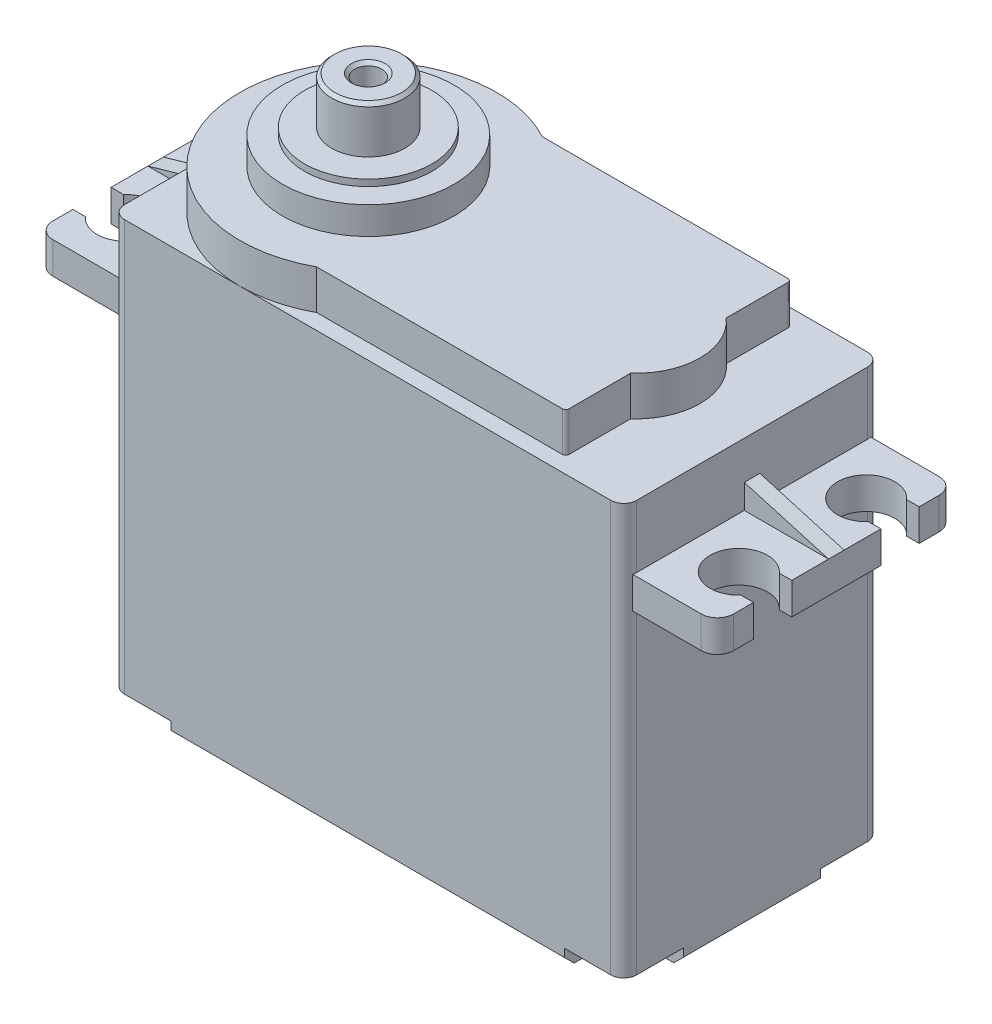
SolidWorks part; units mm, degrees
ref_plane "Front Plane" through (0, 0, 0) normal (0, 0, 1) x (1, 0, 0)
ref_plane "Top Plane" through (0, 0, 0) normal (0, 1, 0) x (1, 0, 0)
ref_plane "Right Plane" through (0, 0, 0) normal (1, 0, 0) x (0, 0, -1)
sketch "Sketch1" plane through (0, 0, 0) normal (0, 1, 0) x (1, 0, 0)
  line L0 (0, 9.0424) -> (0, -9.0424)
  line L1 (1.016, -10.0584) -> (39.116, -10.0584)
  line L2 (40.132, -9.0424) -> (40.132, 9.0424)
  line L3 (39.116, 10.0584) -> (1.016, 10.0584)
  arc A0 (39.116, 10.0584) -> (40.132, 9.0424) centre (39.116, 9.0424) cw
  arc A1 (40.132, -9.0424) -> (39.116, -10.0584) centre (39.116, -9.0424) cw
  arc A2 (1.016, -10.0584) -> (0, -9.0424) centre (1.016, -9.0424) cw
  arc A3 (0, 9.0424) -> (1.016, 10.0584) centre (1.016, 9.0424) cw
  point P7 (40.132, 10.0584)
  point P12 (0, -10.0584)
  point P15 (0, 10.0584)
  dimension "D4" = 1.016
  dimension "D1" = 20.1168
  dimension "D2" = 10.0584
  dimension "D3" = 40.132
extrude "Boss-Extrude1" add sketch "Sketch1" along normal blind 33.6042
sketch "Sketch2" plane through (0, 0, 0) normal (0, -1, 0) x (1, 0, 0)
  line L0 (20.066, 10.0584) -> (20.066, -10.0584) construction
  line L1 (1.016, 10.0584) -> (39.116, 10.0584) construction
  line L2 (39.116, -10.0584) -> (1.016, -10.0584) construction
  line L3 (0, 0) -> (40.132, 0) construction
  line L4 (40.132, 9.0424) -> (40.132, -9.0424) construction
  line L5 (4.6482, 10.0584) -> (4.6482, 7.3533)
  line L6 (35.4838, 10.0584) -> (35.4838, 7.3533)
  line L7 (0, -5.3721) -> (2.667, -5.3721)
  line L8 (0, 5.3721) -> (2.667, 5.3721)
  line L9 (37.465, 5.3721) -> (40.132, 5.3721)
  line L10 (4.6482, -7.3533) -> (4.6482, -10.0584)
  line L11 (0, 5.3721) -> (40.132, 5.3721) construction
  line L12 (37.465, -5.3721) -> (40.132, -5.3721)
  line L13 (4.6482, 10.0584) -> (4.6482, -10.0584) construction
  line L14 (35.4838, -7.3533) -> (35.4838, -10.0584)
  line L15 (0, -5.3721) -> (40.132, -5.3721) construction
  line L16 (0, -5.3721) -> (0, -9.0424)
  line L17 (35.4838, 10.0584) -> (35.4838, -10.0584) construction
  line L18 (35.4838, -10.0584) -> (39.116, -10.0584)
  line L19 (40.132, 5.3721) -> (40.132, 9.0424)
  line L20 (4.6482, 10.0584) -> (1.016, 10.0584)
  line L21 (40.132, -9.0424) -> (40.132, 9.0424)
  line L22 (39.116, 10.0584) -> (1.016, 10.0584)
  line L23 (0, 9.0424) -> (0, -9.0424)
  line L24 (1.016, -10.0584) -> (39.116, -10.0584)
  line L25 (40.132, -9.0424) -> (40.132, -5.3721)
  line L26 (39.116, 10.0584) -> (35.4838, 10.0584)
  line L27 (0, 9.0424) -> (0, 5.3721)
  line L28 (1.016, -10.0584) -> (4.6482, -10.0584)
  arc A0 (2.667, -5.3721) -> (4.6482, -7.3533) centre (2.667, -7.3533) cw
  arc A1 (35.4838, -7.3533) -> (37.465, -5.3721) centre (37.465, -7.3533) cw
  arc A2 (37.465, 5.3721) -> (35.4838, 7.3533) centre (37.465, 7.3533) cw
  arc A3 (4.6482, 7.3533) -> (2.667, 5.3721) centre (2.667, 7.3533) cw
  arc A8 (39.116, -10.0584) -> (40.132, -9.0424) centre (39.116, -9.0424) ccw
  arc A9 (40.132, 9.0424) -> (39.116, 10.0584) centre (39.116, 9.0424) ccw
  arc A10 (1.016, 10.0584) -> (0, 9.0424) centre (1.016, 9.0424) ccw
  arc A11 (0, -9.0424) -> (1.016, -10.0584) centre (1.016, -9.0424) ccw
  arc A12 (39.116, -10.0584) -> (40.132, -9.0424) centre (39.116, -9.0424) ccw
  arc A13 (40.132, 9.0424) -> (39.116, 10.0584) centre (39.116, 9.0424) ccw
  arc A14 (1.016, 10.0584) -> (0, 9.0424) centre (1.016, 9.0424) ccw
  arc A15 (0, -9.0424) -> (1.016, -10.0584) centre (1.016, -9.0424) ccw
  point P27 (35.4838, -5.3721)
  dimension "D5" = 1.9812
  dimension "D1" = 15.4178
  dimension "D2" = 15.4178
  dimension "D3" = 5.3721
  dimension "D4" = 5.3721
  dimension "D6" = 0
extrude "Cut-Extrude1" cut sketch "Sketch2" against normal blind 1.397
chamfer "Chamfer1" distance 0.762 angle 45 4 edges at (0, 0, 0) (20.066, 0, -10.0584) (40.132, 0, 0) (20.066, 0, 10.0584)
sketch "Sketch3" plane through (40.132, 0, 0) normal (1, 0, 0) x (0, 0, -1)
  line L1 (-9.3218, 28.702) -> (9.3218, 28.702)
  line L2 (-9.0424, 26.2128) -> (9.0424, 26.2128)
  line L3 (-9.3218, 26.2128) -> (9.3218, 26.2128)
  line L4 (0, 39.7789) -> (0, -7.6498) construction
  line L5 (-9.3218, 28.702) -> (-9.3218, 26.2128)
  line L6 (9.3218, 28.702) -> (9.3218, 26.2128)
  line L7 (-9.0424, 28.702) -> (9.0424, 28.702) construction
  line L8 (-9.3218, 39.7789) -> (-9.3218, -7.6498) construction
  line L9 (-9.0424, 26.2128) -> (9.0424, 26.2128) construction
  line L10 (9.3218, 39.7789) -> (9.3218, -7.6498) construction
  dimension "D1" = 7.3914
  dimension "D2" = 9.3218
  dimension "D3" = 2.4892
  dimension "D4" = 9.3218
extrude "Boss-Extrude2" add sketch "Sketch3" along normal mid plane 13.208
sketch "Sketch4" plane through (0, 0, 0) normal (-1, 0, 0) x (0, 0, 1)
  line L0 (9.0424, 26.2128) -> (-9.0424, 26.2128) construction
  line L1 (-9.3218, 26.2128) -> (-9.3218, 28.702) construction
  line L2 (-9.0424, 28.702) -> (9.0424, 28.702) construction
  line L3 (9.3218, 28.702) -> (9.3218, 26.2128) construction
  line L4 (9.3218, 26.2128) -> (-9.3218, 26.2128)
  line L5 (-9.3218, 26.2128) -> (-9.3218, 28.702)
  line L6 (-9.3218, 28.702) -> (9.3218, 28.702)
  line L7 (9.3218, 28.702) -> (9.3218, 26.2128)
extrude "Boss-Extrude3" add sketch "Sketch4" along normal mid plane 13.208
fillet "Fillet1" radius 1.27 4 edges at (-6.604, 27.4574, 9.3218) (-6.604, 27.4574, -9.3218) (46.736, 27.4574, -9.3218) (46.736, 27.4574, 9.3218)
sketch "Sketch5" plane through (0, 28.702, 0) normal (0, 1, 0) x (1, 0, 0)
  line L0 (-9.1456, 0) -> (53.3851, 0) construction
  line L1 (20.066, 10.0584) -> (20.066, -10.0584) construction
  line L2 (39.116, 10.0584) -> (1.016, 10.0584) construction
  line L3 (1.016, -10.0584) -> (39.116, -10.0584) construction
  line L4 (-9.1456, -4.9911) -> (-3.9497, -4.9911) construction
  line L5 (-9.1456, 4.9911) -> (-3.9497, 4.9911) construction
  line L6 (-3.9497, 10.0584) -> (-3.9497, 4.9911) construction
  line L7 (44.0817, 10.0584) -> (44.0817, 4.9911) construction
  line L8 (-3.9497, -4.9911) -> (-3.9497, -10.0584) construction
  line L9 (44.0817, -4.9911) -> (44.0817, -10.0584) construction
  line L10 (-3.9497, 10.0584) -> (-3.9497, -10.0584) construction
  line L11 (44.0817, -4.9911) -> (53.3851, -4.9911) construction
  line L12 (44.0817, 10.0584) -> (44.0817, -10.0584) construction
  line L13 (44.0817, 4.9911) -> (53.3851, 4.9911) construction
  line L14 (-9.1456, -4.9911) -> (53.3851, -4.9911) construction
  line L15 (-6.604, 3.4925) -> (-5.6252, 3.4925)
  line L16 (-9.1456, 4.9911) -> (53.3851, 4.9911) construction
  line L17 (-6.604, -6.4897) -> (-5.6252, -6.4897)
  line L18 (45.7572, -6.4897) -> (46.736, -6.4897)
  line L19 (45.7572, 3.4925) -> (46.736, 3.4925)
  line L20 (-6.604, 6.4897) -> (-5.6252, 6.4897)
  line L21 (-6.604, -3.4925) -> (-5.6252, -3.4925)
  line L22 (45.7572, -3.4925) -> (46.736, -3.4925)
  line L23 (45.7572, 6.4897) -> (46.736, 6.4897)
  line L24 (-6.604, -8.0518) -> (-6.604, 8.0518) construction
  line L25 (46.736, 8.0518) -> (46.736, -8.0518) construction
  line L26 (-6.604, -6.4897) -> (-6.604, -3.4925)
  line L27 (46.736, 6.4897) -> (46.736, 3.4925)
  line L28 (-9.1456, 6.4897) -> (-3.9497, 6.4897) construction
  line L29 (-9.1456, -6.4897) -> (-3.9497, -6.4897) construction
  line L30 (44.0817, -6.4897) -> (53.3851, -6.4897) construction
  line L31 (44.0817, 6.4897) -> (53.3851, 6.4897) construction
  line L32 (46.736, -3.4925) -> (46.736, -6.4897)
  line L33 (44.0817, 3.4925) -> (53.3851, 3.4925) construction
  line L34 (44.0817, -3.4925) -> (53.3851, -3.4925) construction
  line L35 (-9.1456, -3.4925) -> (-3.9497, -3.4925) construction
  line L36 (-9.1456, 3.4925) -> (-3.9497, 3.4925) construction
  line L37 (-6.604, 3.4925) -> (-6.604, 6.4897)
  arc A0 (-5.6252, 3.4925) -> (-5.6252, 6.4897) centre (-3.9497, 4.9911) ccw
  arc A1 (-5.6252, -6.4897) -> (-5.6252, -3.4925) centre (-3.9497, -4.9911) ccw
  arc A2 (45.7572, -3.4925) -> (45.7572, -6.4897) centre (44.0817, -4.9911) ccw
  arc A3 (45.7572, 6.4897) -> (45.7572, 3.4925) centre (44.0817, 4.9911) ccw
  dimension "D5" = 4.4958
  dimension "D1" = 4.9911
  dimension "D2" = 4.9911
  dimension "D3" = 24.0157
  dimension "D4" = 24.0157
  dimension "D6" = 1.4986
  dimension "D7" = 1.4986
extrude "Cut-Extrude2" cut sketch "Sketch5" against normal blind 3.048
sketch "Sketch6" plane through (0, 28.702, 0) normal (0, 1, 0) x (1, 0, 0)
  line L0 (-7.6959, 0) -> (49.9058, 0) construction
  line L1 (-6.604, -0.6096) -> (0, -0.6096)
  line L2 (-6.604, 0.6096) -> (0, 0.6096)
  line L3 (-6.604, -3.4925) -> (-6.604, 3.4925) construction
  line L4 (0, 9.0424) -> (0, -9.0424) construction
  line L5 (40.132, -9.0424) -> (40.132, 9.0424) construction
  line L6 (46.736, 3.4925) -> (46.736, -3.4925) construction
  line L7 (-6.604, -0.6096) -> (-6.604, 0.6096)
  line L8 (0, 0.6096) -> (0, -0.6096)
  line L9 (40.132, -0.6096) -> (40.132, 0.6096)
  line L10 (46.736, 0.6096) -> (46.736, -0.6096)
  line L11 (-7.6959, 0.6096) -> (49.9058, 0.6096) construction
  line L12 (-7.6959, -0.6096) -> (49.9058, -0.6096) construction
  line L13 (40.132, 0.6096) -> (46.736, 0.6096)
  line L14 (40.132, -0.6096) -> (46.736, -0.6096)
  dimension "D1" = 0.6096
  dimension "D2" = 0.6096
extrude "Boss-Extrude4" add sketch "Sketch6" along normal blind 1.905
sketch "Sketch7" plane through (0, 0, 0.6096) normal (0, 0, 1) x (1, 0, 0)
  line L0 (40.132, 30.607) -> (46.736, 28.702)
  line L1 (0, 30.607) -> (-6.604, 28.702)
  line L4 (-6.604, 28.702) -> (0, 28.702)
  line L5 (0, 28.702) -> (0, 30.607)
  line L6 (0, 30.607) -> (-6.604, 30.607)
  line L7 (-6.604, 30.607) -> (-6.604, 28.702)
  line L10 (0, 30.607) -> (-6.604, 30.607)
  line L11 (-6.604, 30.607) -> (-6.604, 28.702)
  line L12 (40.132, 28.702) -> (46.736, 28.702)
  line L13 (46.736, 28.702) -> (46.736, 30.607)
  line L14 (46.736, 30.607) -> (40.132, 30.607)
  line L15 (40.132, 30.607) -> (40.132, 28.702)
  line L17 (46.736, 28.702) -> (46.736, 30.607)
  line L18 (46.736, 30.607) -> (40.132, 30.607)
  dimension "D1" = 0
  dimension "D2" = 0
extrude "Cut-Extrude3" cut sketch "Sketch7" against normal blind 1.905
sketch "Sketch8" plane through (0, 33.6042, 0) normal (0, 1, 0) x (1, 0, 0)
  line L0 (-8.5657, 0) -> (49.6158, 0) construction
  line L1 (14.8584, -8.8392) -> (34.1122, -8.8392)
  line L2 (14.8584, 8.8392) -> (34.1122, 8.8392)
  line L4 (-8.5657, 8.8392) -> (49.6158, 8.8392) construction
  line L5 (10.0584, 9.0424) -> (10.0584, -9.0424)
  line L6 (10.0584, 9.0424) -> (10.0584, -9.0424) construction
  line L7 (-8.5657, -8.8392) -> (49.6158, -8.8392) construction
  line L8 (34.3662, -3.7413) -> (34.3662, -8.5852)
  line L9 (34.3662, 9.0424) -> (34.3662, -9.0424)
  line L10 (34.3662, 8.5852) -> (34.3662, 3.7413)
  arc A0 (14.8584, 8.8392) -> (14.8584, -8.8392) centre (10.0584, 0) ccw
  arc A1 (34.3662, -3.7413) -> (34.3662, 3.7413) centre (31.0626, 0) ccw
  arc A2 (34.1122, -8.8392) -> (34.3662, -8.5852) centre (34.1122, -8.5852) ccw
  arc A3 (34.3662, 8.5852) -> (34.1122, 8.8392) centre (34.1122, 8.5852) ccw
  dimension "D5" = 9.9822
  dimension "D6" = 0.254
  dimension "D1" = 10.0584
  dimension "D2" = 8.8392
  dimension "D3" = 8.8392
  dimension "D4" = 34.3662
extrude "Boss-Extrude5" add sketch "Sketch8" along normal blind 3.0988
sketch "Sketch9" plane through (0, 36.703, 0) normal (0, 1, 0) x (1, 0, 0)
  circle A0 centre (10.0584, 0) radius 6.731
  dimension "D1" = 13.462
extrude "Boss-Extrude6" add sketch "Sketch9" along normal blind 2.159
sketch "Sketch10" plane through (0, 38.862, 0) normal (0, 1, 0) x (1, 0, 0)
  circle A0 centre (10.0584, 0) radius 4.9911
  dimension "D1" = 9.9822
extrude "Boss-Extrude7" add sketch "Sketch10" along normal blind 0.508
sketch "Sketch11" plane through (0, 39.37, 0) normal (0, 1, 0) x (1, 0, 0)
  circle A0 centre (10.0584, 0) radius 2.8702
  dimension "D1" = 5.7404
extrude "Boss-Extrude8" add sketch "Sketch11" along normal blind 3.6576
sketch "Sketch12" plane through (0, 43.0276, 0) normal (0, 1, 0) x (1, 0, 0)
  circle A0 centre (10.0584, 0) radius 1.0668
  dimension "D1" = 2.1336
extrude "Cut-Extrude4" cut sketch "Sketch12" against normal blind 5.08
chamfer "Chamfer2" distance 0.254 angle 45 2 edges at (10.0584, 43.0276, 2.8702) (10.0584, 43.0276, 1.0668)
